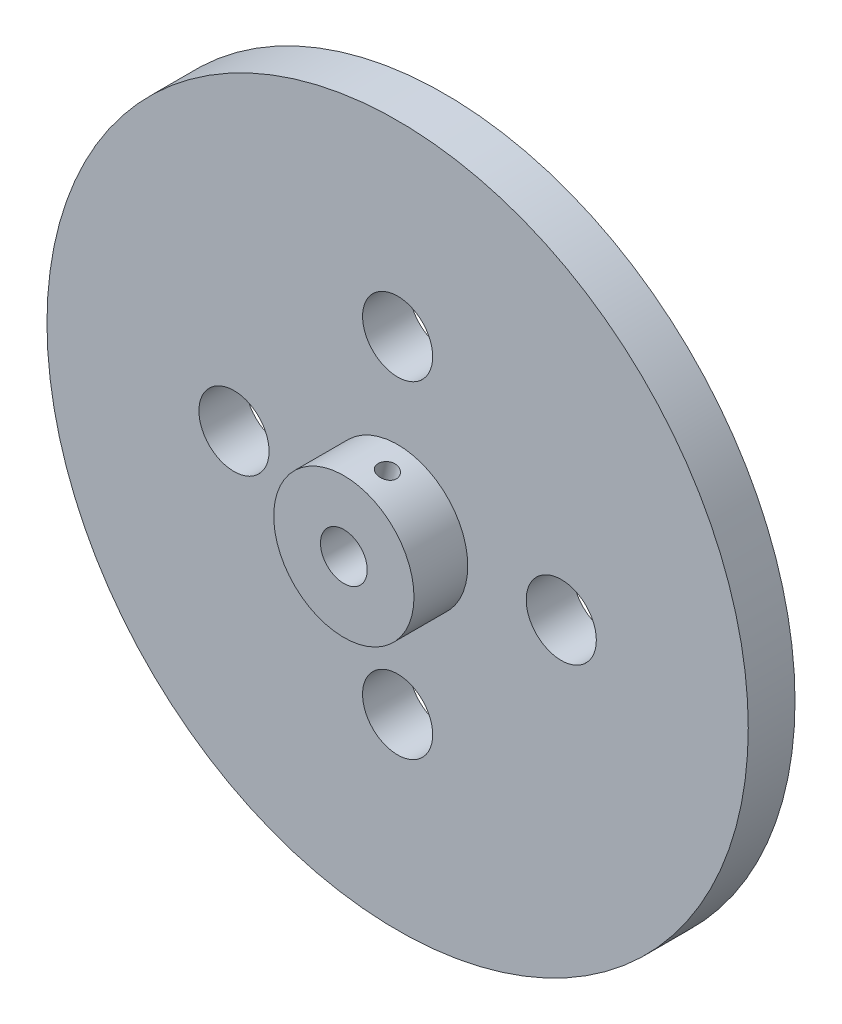
SolidWorks part; units mm, degrees
material "铸造合金钢"
ref_plane "前视基准面" through (0, 0, 0) normal (0, 0, 1) x (1, 0, 0)
ref_plane "上视基准面" through (0, 0, 0) normal (0, 1, 0) x (1, 0, 0)
ref_plane "右视基准面" through (0, 0, 0) normal (1, 0, 0) x (0, 0, -1)
sketch "草图1" plane through (0, 0, 0) normal (0, 0, 1) x (1, 0, 0)
  circle A0 centre (0, 0) radius 15
  dimension "D1" = 30
extrude "凸台-拉伸1" add sketch "草图1" along normal blind 2
sketch "草图2" plane through (0, 0, 2) normal (0, 0, 1) x (1, 0, 0)
  circle A0 centre (0, 0) radius 3
  circle A1 centre (0, 0) radius 1
  dimension "D1" = 2
  dimension "D2" = 6
extrude "凸台-拉伸2" add sketch "草图2" along normal blind 2.3
sketch "草图3" plane through (0, 0, 2) normal (0, 0, 1) x (1, 0, 0)
  circle A0 centre (0, 0) radius 7 construction
  circle A1 centre (0, 7) radius 1
  circle A2 centre (7, 0) radius 1
  circle A3 centre (0, -7) radius 1
  circle A4 centre (-7, 0) radius 1
  point P13 (0, 0)
  dimension "D1" = 14
  dimension "D2" = 2
  dimension "D3" = 4
extrude "切除-拉伸1" cut sketch "草图3" against normal blind 6 contours A1 | A4 | A2 | A3
sketch "草图4" plane through (0, 0, 0) normal (0, 0, -1) x (-1, 0, 0)
  circle A0 centre (0, 0) radius 1
  dimension "D1" = 2
extrude "切除-拉伸2" cut sketch "草图4" against normal through all
sketch "草图5" plane through (0, 0, 2) normal (0, 0, 1) x (1, 0, 0)
  circle A0 centre (0, 7) radius 1.5
  circle A1 centre (-7, 0) radius 1.5
  circle A2 centre (7, 0) radius 1.5
  circle A3 centre (0, -7) radius 1.5
extrude "切除-拉伸3" cut sketch "草图5" against normal blind 10
extrude "切除-拉伸4" cut sketch "草图6" against normal blind 1.1 and the other way blind 2
sketch "草图6" plane through (64.5215, -12.7549, 46.9763) normal (-0.2236, -0.9747, 0) x (0, 0, -1)
  circle A0 centre (43.8722, -65.74) radius 0.4
